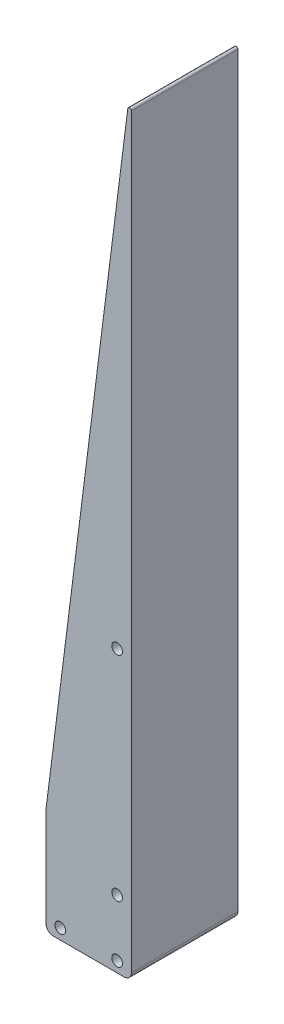
SolidWorks part; units mm, degrees
ref_plane "前视基准面" through (0, 0, 0) normal (0, 0, 1) x (1, 0, 0)
ref_plane "上视基准面" through (0, 0, 0) normal (0, 1, 0) x (1, 0, 0)
ref_plane "右视基准面" through (0, 0, 0) normal (1, 0, 0) x (0, 0, -1)
other "Configuration Table"
sketch "草图1" plane through (0, 0, 0) normal (0, 0, 1) x (1, 0, 0)
  line L0 (23.0039, 212.1145) -> (0.0158, 30.1248)
  line L1 (2, 0) -> (22, 0)
  line L2 (0, 2) -> (0, 29.8742)
  line L4 (24, 2) -> (24, 212.0519)
  circle A0 centre (20, 3) radius 1.5
  circle A1 centre (4, 3) radius 1.5
  circle A3 centre (20, 19) radius 1.5
  circle A4 centre (4, 19) radius 1.5 [skipped]
  arc A5 (24, 212.0519) -> (23.0039, 212.1145) centre (23.5, 212.0519) ccw
  arc A6 (0, 29.8742) -> (0.0158, 30.1248) centre (2, 29.8742) cw
  arc A7 (24, 2) -> (22, 0) centre (22, 2) cw
  arc A8 (2, 0) -> (0, 2) centre (2, 2) cw
  point P22 (24, 0)
  point P25 (0, 0)
  dimension "D3" = 3
  dimension "D9" = 0.5
  dimension "D8" = 2
  dimension "D1" = 24
  dimension "D2" = 183.4359
  dimension "D4" = 4
  dimension "D5" = 3
  dimension "D6" = 2
  dimension "D7" = 2
extrude "凸台-拉伸2" add sketch "草图1" along normal blind 30
sketch "草图2" plane through (0, 0, 0) normal (0, 0, -1) x (-1, 0, 0)
  circle A0 centre (-20, 79) radius 1.5
extrude "切除-拉伸1" cut sketch "草图2" against normal through all
